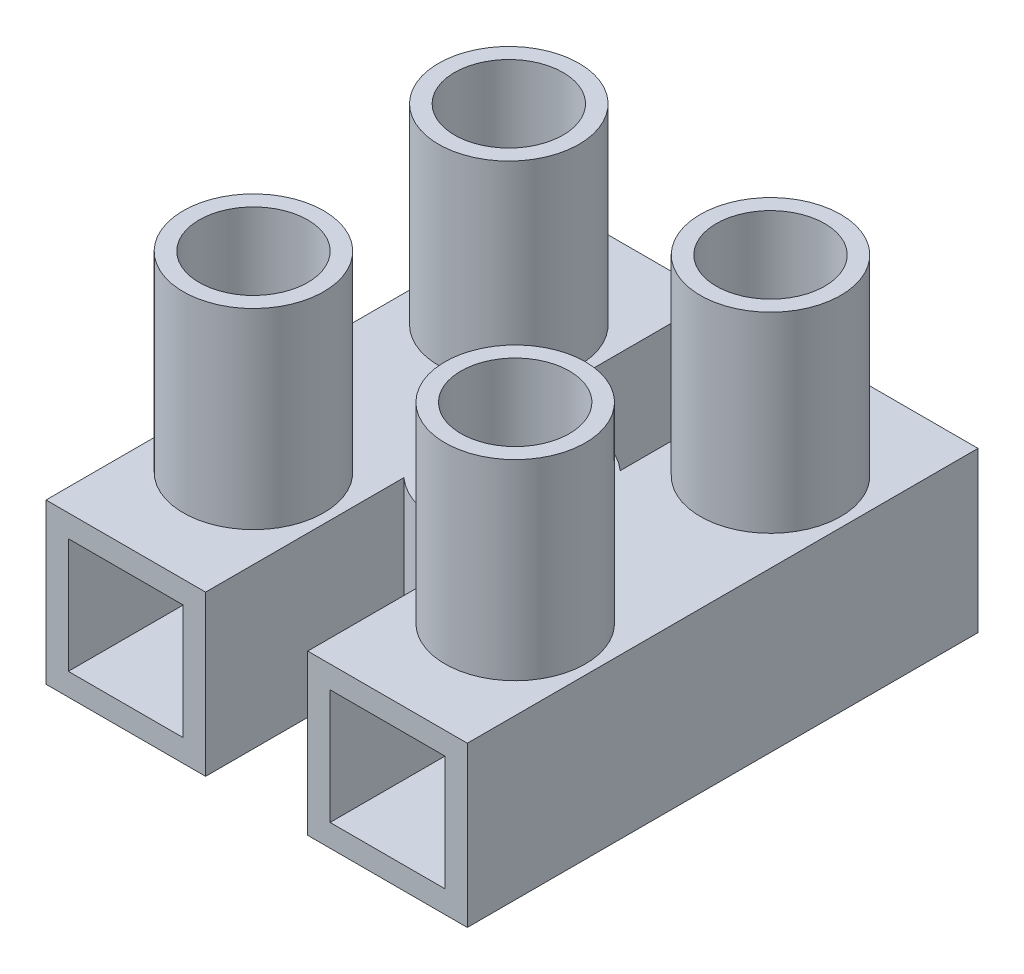
SolidWorks part; units mm, degrees
material "Nylon 6/10"
ref_plane "Front Plane" through (0, 0, 0) normal (0, 0, 1) x (1, 0, 0)
ref_plane "Top Plane" through (0, 0, 0) normal (0, 1, 0) x (1, 0, 0)
ref_plane "Right Plane" through (0, 0, 0) normal (1, 0, 0) x (0, 0, -1)
sketch "Sketch1" plane through (0, 0, 0) normal (0, 1, 0) x (1, 0, 0)
  line L0 (-2.032, -2.2718) -> (-2.032, -10.16)
  line L1 (2.032, 10.16) -> (8.382, 10.16)
  line L2 (2.032, 10.16) -> (2.032, 2.2718)
  line L3 (2.032, -10.16) -> (8.382, -10.16)
  line L4 (8.382, 10.16) -> (8.382, -10.16)
  line L5 (-8.382, 10.16) -> (-2.032, 10.16)
  line L6 (-8.382, 10.16) -> (-8.382, -10.16)
  line L7 (-8.382, -10.16) -> (-2.032, -10.16)
  line L8 (-2.032, 10.16) -> (-2.032, 2.2718)
  line L9 (2.032, -2.2718) -> (2.032, -10.16)
  arc A1 (-2.032, -2.2718) -> (2.032, -2.2718) centre (0, 0) ccw
  arc A2 (2.032, 2.2718) -> (-2.032, 2.2718) centre (0, 0) ccw
  point P12 (-8.382, 0)
  point P13 (8.382, 0)
  dimension "D6" = 6.096
  dimension "D1" = 20.32
  dimension "D2" = 6.35
  dimension "D3" = 6.35
  dimension "D4" = 20.32
extrude "Boss-Extrude1" add sketch "Sketch1" against normal blind 6.35
sketch "Sketch2" plane through (0, 0, 0) normal (0, 1, 0) x (1, 0, 0)
  circle A0 centre (0, 0) radius 2.286
  dimension "D1" = 4.572
extrude "Cut-Extrude1" cut sketch "Sketch2" against normal through all
sketch "Sketch3" plane through (0, 0, 10.16) normal (0, 0, 1) x (1, 0, 0)
  line L0 (-8.382, -6.35) -> (-8.382, 0) construction
  line L1 (-7.493, -0.889) -> (-2.921, -0.889)
  line L2 (-7.493, -0.889) -> (-7.493, -5.461)
  line L3 (-7.493, -5.461) -> (-2.921, -5.461)
  line L4 (-2.921, -0.889) -> (-2.921, -5.461)
  line L5 (2.921, -0.889) -> (7.493, -0.889)
  line L6 (2.921, -0.889) -> (2.921, -5.461)
  line L7 (2.921, -5.461) -> (7.493, -5.461)
  line L8 (7.493, -0.889) -> (7.493, -5.461)
  line L9 (-8.382, 0) -> (-2.032, 0) construction
  line L10 (2.032, 0) -> (8.382, 0) construction
  point P8 (-7.493, -3.175)
  point P11 (-8.382, -3.175)
  point P12 (2.921, -3.175)
  point P15 (-5.207, 0)
  point P16 (-5.207, -0.889)
  point P19 (5.207, 0)
  point P20 (5.207, -0.889)
  dimension "D1" = 4.572
  dimension "D2" = 4.572
  dimension "D3" = 4.572
  dimension "D4" = 4.572
extrude "Cut-Extrude2" cut sketch "Sketch3" against normal blind 7.62
sketch "Sketch4" plane through (0, 0, -10.16) normal (0, 0, -1) x (-1, 0, 0)
  line L0 (-8.382, -6.35) -> (-8.382, 0) construction
  line L1 (-7.493, -0.889) -> (-2.921, -0.889)
  line L2 (-7.493, -0.889) -> (-7.493, -5.461)
  line L3 (-7.493, -5.461) -> (-2.921, -5.461)
  line L4 (-2.921, -0.889) -> (-2.921, -5.461)
  line L5 (2.921, -0.889) -> (7.493, -0.889)
  line L6 (2.921, -0.889) -> (2.921, -5.461)
  line L7 (2.921, -5.461) -> (7.493, -5.461)
  line L8 (7.493, -0.889) -> (7.493, -5.461)
  line L9 (-8.382, 0) -> (-2.032, 0) construction
  line L10 (2.032, 0) -> (8.382, 0) construction
  point P10 (-8.382, -3.175)
  point P11 (-7.493, -3.175)
  point P12 (2.921, -3.175)
  point P15 (-5.207, 0)
  point P16 (-5.207, -0.889)
  point P19 (5.207, 0)
  point P20 (5.207, -0.889)
  dimension "D1" = 4.572
  dimension "D2" = 4.572
  dimension "D3" = 4.572
  dimension "D4" = 4.572
extrude "Cut-Extrude3" cut sketch "Sketch4" against normal blind 7.62
sketch "Sketch5" plane through (0, 0, 0) normal (0, 1, 0) x (1, 0, 0)
  line L0 (8.382, 10.16) -> (2.032, 10.16) construction
  line L1 (2.032, -10.16) -> (8.382, -10.16) construction
  line L2 (-2.032, 10.16) -> (-8.382, 10.16) construction
  circle A0 centre (-5.207, -5.08) radius 2.794
  circle A1 centre (-5.207, 5.08) radius 2.794
  circle A2 centre (5.207, 5.08) radius 2.794
  circle A3 centre (5.207, -5.08) radius 2.794
  circle A4 centre (-5.207, 5.08) radius 2.159
  circle A5 centre (5.207, 5.08) radius 2.159
  circle A6 centre (5.207, -5.08) radius 2.159
  circle A7 centre (-5.207, -5.08) radius 2.159
  point P13 (5.207, 10.16)
  point P16 (-5.207, 10.16)
  dimension "D1" = 5.588
  dimension "D2" = 5.08
  dimension "D3" = 5.588
  dimension "D4" = 5.08
  dimension "D5" = 5.588
  dimension "D6" = 5.588
  dimension "D7" = 4.318
  dimension "D8" = 4.318
  dimension "D9" = 4.318
  dimension "D10" = 4.318
extrude "Boss-Extrude2" add sketch "Sketch5" along normal blind 7.62
